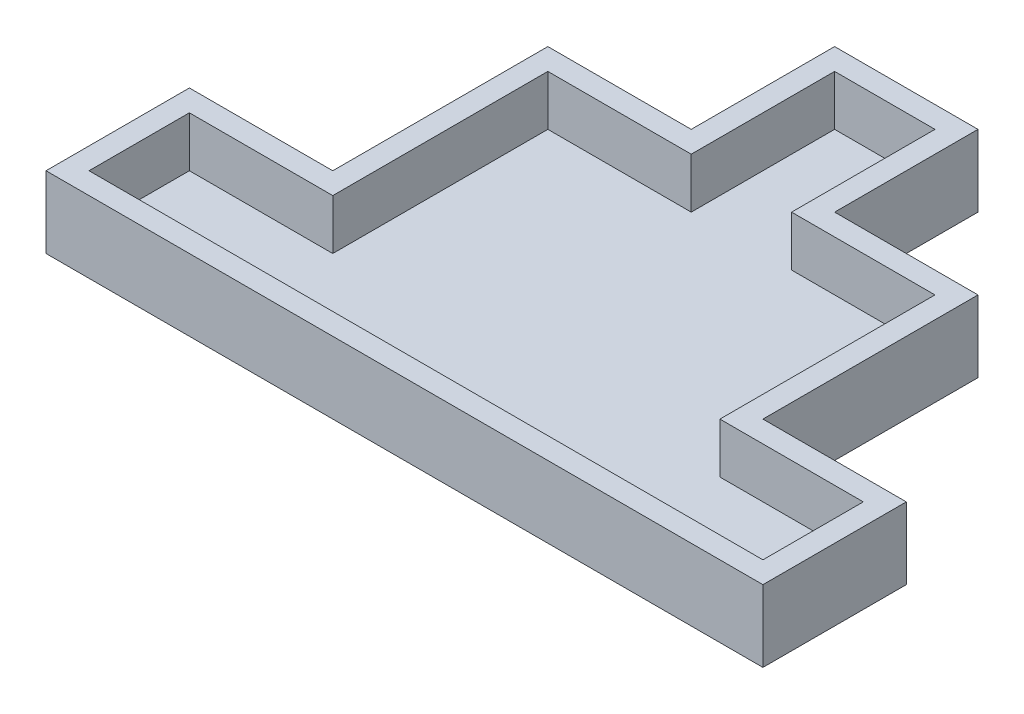
SolidWorks part; units mm, degrees
ref_plane "Front Plane" through (0, 0, 0) normal (0, 0, 1) x (1, 0, 0)
ref_plane "Top Plane" through (0, 0, 0) normal (0, 1, 0) x (1, 0, 0)
ref_plane "Right Plane" through (0, 0, 0) normal (1, 0, 0) x (0, 0, -1)
sketch "Sketch1" plane through (0, 0, 0) normal (0, 1, 0) x (1, 0, 0)
  line L0 (0, 0) -> (0, 65778.7113) construction
  line L1 (75, 0) -> (-75, 0)
  line L2 (-75, 0) -> (-75, 30)
  line L3 (-75, 30) -> (-45, 30)
  line L4 (-45, 30) -> (-45, 75)
  line L5 (-45, 75) -> (-15, 75)
  line L6 (-15, 75) -> (-15, 105)
  line L7 (-15, 105) -> (15, 105)
  line L8 (15, 75) -> (15, 105)
  line L9 (45, 75) -> (15, 75)
  line L10 (45, 30) -> (45, 75)
  line L11 (75, 30) -> (45, 30)
  line L12 (75, 0) -> (75, 30)
  point P12 (0, 105)
  point P13 (0, 0)
  dimension "D1" = 75
  dimension "D2" = 30
  dimension "D3" = 30
  dimension "D4" = 45
  dimension "D5" = 30
  dimension "D6" = 30
  dimension "D7" = 15
extrude "Boss-Extrude1" add sketch "Sketch1" along normal blind 15
shell "Shell2" thickness 4.5
